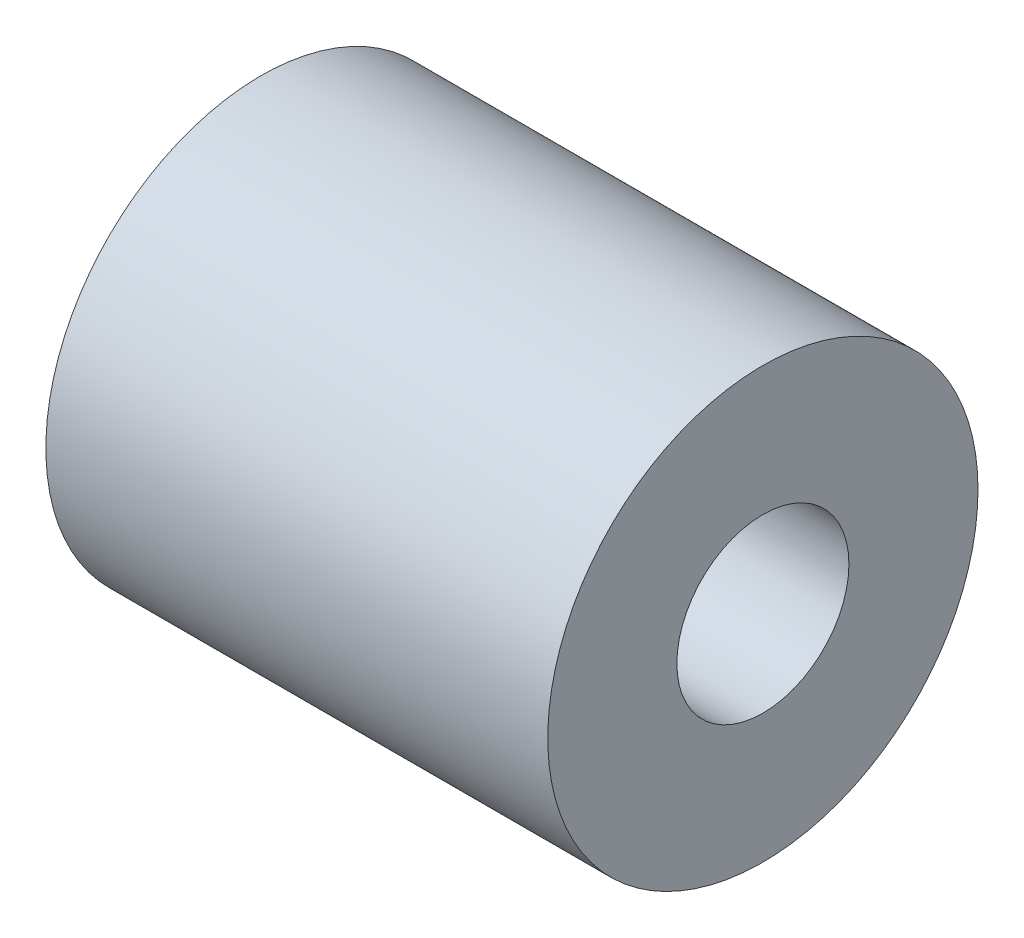
SolidWorks part; units mm, degrees
ref_plane "Front Plane" through (0, 0, 0) normal (0, 0, 1) x (1, 0, 0)
ref_plane "Top Plane" through (0, 0, 0) normal (0, 1, 0) x (1, 0, 0)
ref_plane "Right Plane" through (0, 0, 0) normal (1, 0, 0) x (0, 0, -1)
sketch "Sketch1" plane through (0, 0, 0) normal (1, 0, 0) x (0, 0, -1)
  circle A0 centre (0, 0) radius 15
  dimension "D1" = 30
extrude "Boss-Extrude1" add sketch "Sketch1" along normal mid plane 35
sketch "Sketch2" plane through (17.5, 0, 0) normal (1, 0, 0) x (0, 0, -1)
  circle A0 centre (0, 0) radius 6
  dimension "D1" = 12
extrude "Cut-Extrude1" cut sketch "Sketch2" against normal blind 17.5
sketch "Sketch3" plane through (-17.5, 0, 0) normal (-1, 0, 0) x (0, 0, 1)
  circle A0 centre (0, 0) radius 4
  dimension "D1" = 8
extrude "Cut-Extrude2" cut sketch "Sketch3" against normal blind 17.5
equation "\"WheelDiameter\" = 150mm"
equation "\"WheelRadius\" = \"WheelDiameter\" / 2"
equation "\"DT_WheelWidth\" = 45mm"
equation "\"DT_Wheelbase\" = 300mm"
equation "\"DT_ShaftDiameter\" = 12mm"
equation "\"DT_FrontShaftLength\" = 180mm"
equation "\"DT_RearShaftLength\" = 200mm"
equation "\"DT_BearingWidth\" = 20mm"
equation "\"DT_BearingHousingWidth\" = 60mm"
equation "\"DT_BearingHousingHeight\" = 35mm"
equation "\"DT_ChainPitch\" = 9.525mm"
equation "\"DT_SprocketTeeth\" = 18"
equation "\"DT_SprocketPitchDiameter\" = 54.851mm"
equation "\"DT_SprocketOuterDiameter\" = 60mm"
equation "\"DT_SprocketThickness\" = 6mm"
equation "\"DT_SprocketHubDiameter\" = 25mm"
equation "\"DT_SprocketHubLength\" = 20mm"
equation "\"DT_CouplingDiameter\" = 30mm"
equation "\"DT_CouplingLength\" = 35mm"
equation "\"DT_MotorDiameter\" = 60mm"
equation "\"DT_MotorLength\" = 120mm"
equation "\"DT_MotorShaftDiameter\" = 8mm"
equation "\"DT_MotorShaftLength\" = 20mm"
